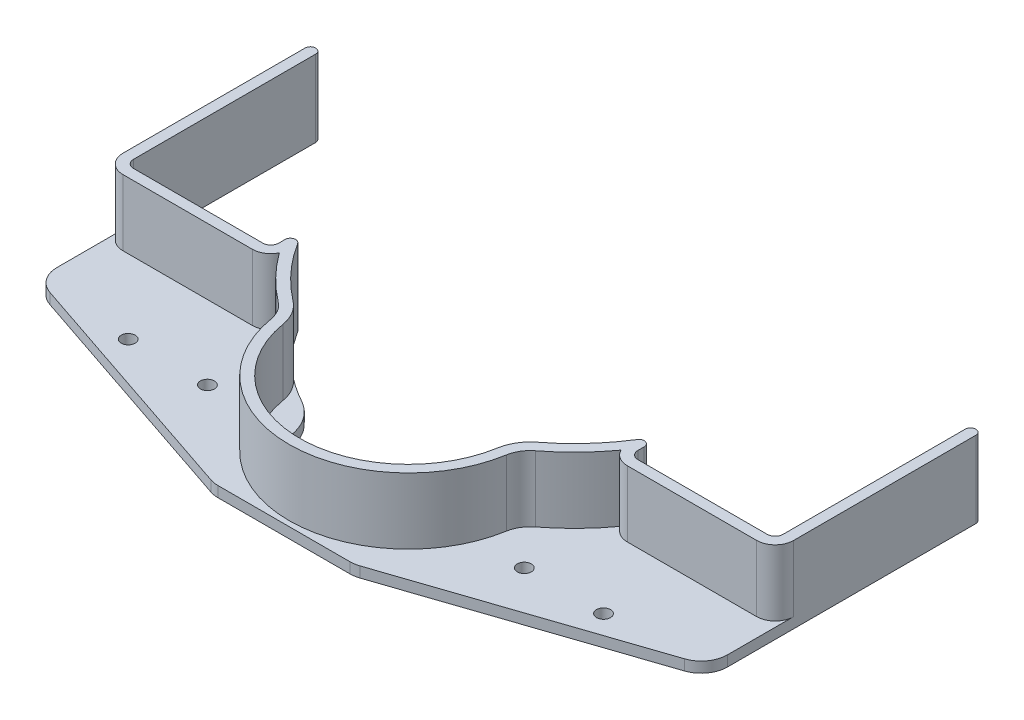
SolidWorks part; units mm, degrees
ref_plane "前视基准面" through (0, 0, 0) normal (0, 0, 1) x (1, 0, 0)
ref_plane "上视基准面" through (0, 0, 0) normal (0, 1, 0) x (1, 0, 0)
ref_plane "右视基准面" through (0, 0, 0) normal (1, 0, 0) x (0, 0, -1)
other "Configuration Table"
sketch "草图2" plane through (0, 0, 0) normal (0, 1, 0) x (1, 0, 0)
  line L0 (0, -0.6047) -> (0, 119.4097) construction
  line L1 (-27.5, 0) -> (0, 30.4097) construction
  line L6 (-27.5, 12.1477) -> (-27.5, 2)
  line L7 (-25.5, 0) -> (25.5, 0)
  line L8 (-1125, 30.4097) -> (-130.7535, 30.4097) construction
  line L9 (-41, 30.4097) -> (0, 94.4019)
  line L10 (1001.5538, 94.4019) -> (0, 94.4019) construction
  line L11 (-127, -112.889) -> (127, -112.889) construction
  line L12 (-127, -112.889) -> (-127, 119.4097) construction
  line L13 (0, 30.4097) -> (-122.3291, 30.4097) construction
  line L14 (28.1932, -15.0668) -> (120.1932, 15.9332)
  line L15 (0, 119.4097) -> (191.7756, 119.4097) construction
  line L16 (-25, -15.5903) -> (25, -15.5903)
  line L17 (27.5, 12.1477) -> (27.5, 2)
  line L18 (-1178.5628, 69.4097) -> (-127, 69.4097) construction
  line L19 (0, 15.4097) -> (-60, 15.4097) construction
  line L20 (-60, 15.4097) -> (-90, 15.4097) construction
  line L23 (-1125.7762, 69.4097) -> (-127, 69.4097) construction
  line L24 (-127, 25.4097) -> (-127, 119.4097)
  line L25 (68, 50.4097) -> (68, 52.8327)
  line L26 (-1250, 119.4097) -> (-127, 119.4097) construction
  line L28 (-123, 119.4097) -> (-123, 50.4097)
  line L29 (120, 47.4097) -> (71, 47.4097)
  line L30 (-68, 27.4097) -> (-68, 52.8327) construction
  line L31 (127, 25.4097) -> (127, 119.4097)
  line L32 (-28.1932, -15.0668) -> (-120.1932, 15.9332)
  line L33 (-120, 47.4097) -> (-71, 47.4097)
  line L34 (-39.6804, 69.4097) -> (925.0396, 69.4097) construction
  line L35 (-123, 94.4019) -> (-1246, 94.4019) construction
  line L36 (-68, 50.4097) -> (-68, 52.8327)
  line L37 (123, 119.4097) -> (123, 50.4097)
  line L38 (-64.3077, 53.8985) -> (0, 94.4019) construction
  line L39 (-90, 15.4097) -> (-60, -8.5903)
  line L40 (-90, 15.4097) -> (-60, 15.4097)
  line L41 (-90, 15.4097) -> (-90, -8.5903)
  line L42 (-90, -8.5903) -> (-60, -8.5903)
  line L43 (-60, 15.4097) -> (-60, -8.5903)
  line L44 (-90, -8.5903) -> (-60, 15.4097)
  arc A0 (-41, 30.4097) -> (41, 30.4097) centre (0, 30.4097) ccw construction
  arc A1 (-64.3077, 53.8985) -> (-36.7872, 27.8985) centre (0, 94.4019) ccw
  arc A4 (-27.5, 12.1477) -> (-36.7872, 27.8985) centre (-45.5, 12.1477) ccw
  arc A5 (-25, -15.5903) -> (-28.1932, -15.0668) centre (-25, -5.5903) cw
  circle A6 centre (-90, 15.4097) radius 2.65
  circle A7 centre (-60, 15.4097) radius 2.65
  arc A9 (-127, 25.4097) -> (-120.1932, 15.9332) centre (-117, 25.4097) ccw
  arc A10 (-68, 52.8327) -> (-64.3077, 53.8985) centre (-66, 52.8327) cw
  arc A22 (-25.5, 0) -> (-27.5, 2) centre (-25.5, 2) cw
  arc A23 (-68, 50.4097) -> (-71, 47.4097) centre (-71, 50.4097) cw
  circle A24 centre (60, 15.4097) radius 2.65
  arc A26 (-120, 47.4097) -> (-123, 50.4097) centre (-120, 50.4097) cw
  arc A29 (-123, 119.4097) -> (-127, 119.4097) centre (-125, 119.4097) ccw
  circle A30 centre (90, 15.4097) radius 2.65
  arc A31 (25, -15.5903) -> (28.1932, -15.0668) centre (25, -5.5903) ccw
  arc A32 (25.5, 0) -> (27.5, 2) centre (25.5, 2) ccw
  arc A33 (27.5, 12.1477) -> (36.7872, 27.8985) centre (45.5, 12.1477) cw
  arc A34 (64.3077, 53.8985) -> (36.7872, 27.8985) centre (0, 94.4019) cw
  arc A35 (68, 50.4097) -> (71, 47.4097) centre (71, 50.4097) ccw
  arc A36 (120, 47.4097) -> (123, 50.4097) centre (120, 50.4097) ccw
  arc A37 (123, 119.4097) -> (127, 119.4097) centre (125, 119.4097) cw
  arc A38 (68, 52.8327) -> (64.3077, 53.8985) centre (66, 52.8327) ccw
  arc A39 (127, 25.4097) -> (120.1932, 15.9332) centre (117, 25.4097) cw
  circle A40 centre (-75, 3.4097) radius 30 construction
  point P1 (0, 0)
  point P26 (-35, -15.5903)
  point P42 (-125, 15.4097)
  point P50 (-72.7485, 69.4097)
  point P66 (-26.6395, -15.5903)
  point P81 (0, -112.889)
  point P86 (-127, 18.2268)
  point P92 (-68, 47.4097)
  point P95 (-123, 47.4097)
  dimension "D6" = 4
  dimension "D13" = 0
  dimension "D19" = 30
  dimension "D24" = 5.3
  dimension "D25" = 5.3
  dimension "D26" = 0
  dimension "D27" = 10
  dimension "D29" = 60
  dimension "D10" = 72
  dimension "D11" = 30
  dimension "D28" = 55
  dimension "D30" = 2
  dimension "D32" = 3
  dimension "D3" = 41
  dimension "D4" = 0
  dimension "D5" = 27.5
  dimension "D7" = 76
  dimension "D8" = 50
  dimension "D9" = 94.4019
  dimension "D12" = 15
  dimension "D14" = 12.1477
  dimension "D15" = 24
  dimension "D16" = 127
  dimension "D17" = 46
  dimension "D18" = 89
  dimension "D20" = 4
  dimension "D21" = 254
  dimension "D22" = 60
  dimension "D23" = 44
  dimension "D31" = 89
  dimension "D33" = 119.4097
  dimension "D34" = 50
extrude "凸台-拉伸1" add sketch "草图2" along normal blind 4 contours A39 L31 A37 L37 A36 L29 A35 L25 A38 A34 A33 L17 A32 L7 A22 L6 A4 A1 A10 L36 A23 L33 A26 L28 A29 L24 A9 L32 L41 A6 L40 A7 L43 A5 L16 A31 L14 A24 A30 | A6 L41 L32 L44 L39 | A7 L40 A6 L39 L44 | A7 L44 L39 L32 L43 | L44 L32 L39
sketch "草图3" plane through (0, 4, 0) normal (0, 1, 0) x (1, 0, 0)
  line L0 (127, 115.4097) -> (127, 50.4097)
  line L1 (120, 43.4097) -> (71, 43.4097)
  line L2 (64.7026, 47.3532) -> (64.7026, 47.3532)
  line L3 (-64.7026, 47.3532) -> (-64.7026, 47.3532)
  line L4 (-71, 43.4097) -> (-120, 43.4097)
  line L5 (-127, 50.4097) -> (-127, 115.4097)
  line L14 (-120.1932, 15.9332) -> (-28.1932, -15.0668)
  line L15 (-25, -15.5903) -> (25, -15.5903)
  line L16 (28.1932, -15.0668) -> (120.1932, 15.9332)
  line L17 (127, 25.4097) -> (127, 119.4097)
  line L18 (123, 119.4097) -> (123, 50.4097)
  line L19 (120, 47.4097) -> (71, 47.4097)
  line L20 (68, 50.4097) -> (68, 52.8327)
  line L21 (27.5, 12.1477) -> (27.5, 2)
  line L22 (25.5, 0) -> (-25.5, 0)
  line L23 (-27.5, 2) -> (-27.5, 12.1477)
  line L24 (-68, 52.8327) -> (-68, 50.4097)
  line L25 (-71, 47.4097) -> (-120, 47.4097)
  line L26 (-123, 50.4097) -> (-123, 119.4097)
  line L27 (-127, 119.4097) -> (-127, 25.4097)
  line L28 (-120.1932, 15.9332) -> (-28.1932, -15.0668)
  line L29 (-25, -15.5903) -> (25, -15.5903)
  line L30 (28.1932, -15.0668) -> (120.1932, 15.9332)
  line L31 (127, 25.4097) -> (127, 119.4097)
  line L32 (123, 119.4097) -> (123, 50.4097)
  line L33 (120, 47.4097) -> (71, 47.4097)
  line L34 (68, 50.4097) -> (68, 52.8327)
  line L35 (27.5, 12.1477) -> (27.5, 2)
  line L36 (25.5, 0) -> (-25.5, 0)
  line L37 (-27.5, 2) -> (-27.5, 12.1477)
  line L38 (-68, 52.8327) -> (-68, 50.4097)
  line L39 (-71, 47.4097) -> (-120, 47.4097)
  line L40 (-123, 50.4097) -> (-123, 119.4097)
  line L41 (-127, 119.4097) -> (-127, 25.4097)
  arc A0 (-40.6101, 24.7011) -> (40.6101, 24.7011) centre (0, 31.5397) ccw
  arc A1 (-40.6101, 24.7011) -> (-46.2696, 34.1099) centre (-55.4018, 22.2102) ccw
  arc A2 (46.2696, 34.1099) -> (40.6101, 24.7011) centre (55.4018, 22.2102) ccw
  arc A3 (127, 115.4097) -> (127, 115.4097) centre (127, 115.4097) ccw
  arc A4 (120, 43.4097) -> (127, 50.4097) centre (120, 50.4097) ccw
  arc A5 (64.7026, 47.3532) -> (71, 43.4097) centre (71, 50.4097) ccw
  arc A6 (64.7026, 47.3532) -> (64.7026, 47.3532) centre (64.7026, 47.3532) ccw
  arc A7 (48.7049, 30.9367) -> (64.7026, 47.3532) centre (0, 94.4019) ccw
  arc A8 (48.7049, 30.9367) -> (44.5545, 24.0369) centre (55.4018, 22.2102) ccw
  arc A9 (-44.5545, 24.0369) -> (44.5545, 24.0369) centre (0, 31.5397) ccw
  arc A10 (-44.5545, 24.0369) -> (-48.7049, 30.9367) centre (-55.4018, 22.2102) ccw
  arc A11 (-64.7026, 47.3532) -> (-48.7049, 30.9367) centre (0, 94.4019) ccw
  arc A12 (-64.7026, 47.3532) -> (-64.7026, 47.3532) centre (-64.7026, 47.3532) ccw
  arc A13 (-71, 43.4097) -> (-64.7026, 47.3532) centre (-71, 50.4097) ccw
  arc A14 (-127, 50.4097) -> (-120, 43.4097) centre (-120, 50.4097) ccw
  arc A15 (-127, 115.4097) -> (-127, 115.4097) centre (-127, 115.4097) ccw
  arc A19 (-28.1932, -15.0668) -> (-25, -15.5903) centre (-25, -5.5903) ccw
  arc A20 (25, -15.5903) -> (28.1932, -15.0668) centre (25, -5.5903) ccw
  arc A21 (120.1932, 15.9332) -> (127, 25.4097) centre (117, 25.4097) ccw
  arc A22 (127, 119.4097) -> (123, 119.4097) centre (125, 119.4097) ccw
  arc A23 (120, 47.4097) -> (123, 50.4097) centre (120, 50.4097) ccw
  arc A24 (68, 50.4097) -> (71, 47.4097) centre (71, 50.4097) ccw
  arc A25 (68, 52.8327) -> (64.3077, 53.8985) centre (66, 52.8327) ccw
  arc A26 (36.7872, 27.8985) -> (64.3077, 53.8985) centre (0, 94.4019) ccw
  arc A27 (36.7872, 27.8985) -> (27.5, 12.1477) centre (45.5, 12.1477) ccw
  arc A28 (25.5, 0) -> (27.5, 2) centre (25.5, 2) ccw
  arc A29 (-27.5, 2) -> (-25.5, 0) centre (-25.5, 2) ccw
  arc A30 (-27.5, 12.1477) -> (-36.7872, 27.8985) centre (-45.5, 12.1477) ccw
  arc A31 (-64.3077, 53.8985) -> (-36.7872, 27.8985) centre (0, 94.4019) ccw
  arc A32 (-64.3077, 53.8985) -> (-68, 52.8327) centre (-66, 52.8327) ccw
  arc A33 (-71, 47.4097) -> (-68, 50.4097) centre (-71, 50.4097) ccw
  arc A34 (-123, 50.4097) -> (-120, 47.4097) centre (-120, 50.4097) ccw
  arc A35 (-123, 119.4097) -> (-127, 119.4097) centre (-125, 119.4097) ccw
  arc A36 (-127, 25.4097) -> (-120.1932, 15.9332) centre (-117, 25.4097) ccw
  arc A37 (-28.1932, -15.0668) -> (-25, -15.5903) centre (-25, -5.5903) ccw
  arc A38 (25, -15.5903) -> (28.1932, -15.0668) centre (25, -5.5903) ccw
  arc A39 (120.1932, 15.9332) -> (127, 25.4097) centre (117, 25.4097) ccw
  arc A40 (127, 119.4097) -> (123, 119.4097) centre (125, 119.4097) ccw
  arc A41 (120, 47.4097) -> (123, 50.4097) centre (120, 50.4097) ccw
  arc A42 (68, 50.4097) -> (71, 47.4097) centre (71, 50.4097) ccw
  arc A43 (68, 52.8327) -> (64.3077, 53.8985) centre (66, 52.8327) ccw
  arc A44 (46.2696, 34.1099) -> (64.3077, 53.8985) centre (0, 94.4019) ccw
  arc A45 (36.7872, 27.8985) -> (27.5, 12.1477) centre (45.5, 12.1477) ccw
  arc A46 (25.5, 0) -> (27.5, 2) centre (25.5, 2) ccw
  arc A47 (-27.5, 2) -> (-25.5, 0) centre (-25.5, 2) ccw
  arc A48 (-27.5, 12.1477) -> (-36.7872, 27.8985) centre (-45.5, 12.1477) ccw
  arc A49 (-64.3077, 53.8985) -> (-46.2696, 34.1099) centre (0, 94.4019) ccw
  arc A50 (-64.3077, 53.8985) -> (-68, 52.8327) centre (-66, 52.8327) ccw
  arc A51 (-71, 47.4097) -> (-68, 50.4097) centre (-71, 50.4097) ccw
  arc A52 (-123, 50.4097) -> (-120, 47.4097) centre (-120, 50.4097) ccw
  arc A53 (-123, 119.4097) -> (-127, 119.4097) centre (-125, 119.4097) ccw
  arc A54 (-127, 25.4097) -> (-120.1932, 15.9332) centre (-117, 25.4097) ccw
  line M39 (127, 25.4097) -> (127, 119.4097)
  arc M40 (127, 119.4097) -> (123, 119.4097) centre (125, 119.4097) ccw
  line M41 (123, 119.4097) -> (123, 50.4097)
  arc M42 (123, 50.4097) -> (120, 47.4097) centre (120, 50.4097) cw
  line M43 (120, 47.4097) -> (71, 47.4097)
  arc M44 (71, 47.4097) -> (68, 50.4097) centre (71, 50.4097) cw
  line M45 (68, 50.4097) -> (68, 52.8327)
  arc M46 (68, 52.8327) -> (64.3077, 53.8985) centre (66, 52.8327) ccw
  arc M47 (64.3077, 53.8985) -> (36.7872, 27.8985) centre (0, 94.4019) cw
  arc M55 (-36.7872, 27.8985) -> (-64.3077, 53.8985) centre (0, 94.4019) cw
  arc M56 (-64.3077, 53.8985) -> (-68, 52.8327) centre (-66, 52.8327) ccw
  line M57 (-68, 52.8327) -> (-68, 50.4097)
  arc M58 (-68, 50.4097) -> (-71, 47.4097) centre (-71, 50.4097) cw
  line M59 (-71, 47.4097) -> (-120, 47.4097)
  arc M60 (-120, 47.4097) -> (-123, 50.4097) centre (-120, 50.4097) cw
  line M61 (-123, 50.4097) -> (-123, 119.4097)
  arc M62 (-123, 119.4097) -> (-127, 119.4097) centre (-125, 119.4097) ccw
  line M63 (-127, 119.4097) -> (-127, 25.4097)
  dimension "D1" = 0
  dimension "D2" = 15
  dimension "D3" = 15
  dimension "D5" = 0
  dimension "D4" = 4
extrude "凸台-拉伸2" add sketch "草图3" along normal blind 25 contours A14 L4 A13 A11 A10 A9 A8 A7 A5 L1 A4 A2 A0 A1 M63 M39 M40 M41 M42 M43 M44 M45 M46 M47 M55 M56 M57 M58 M59 M60 M61 M62
